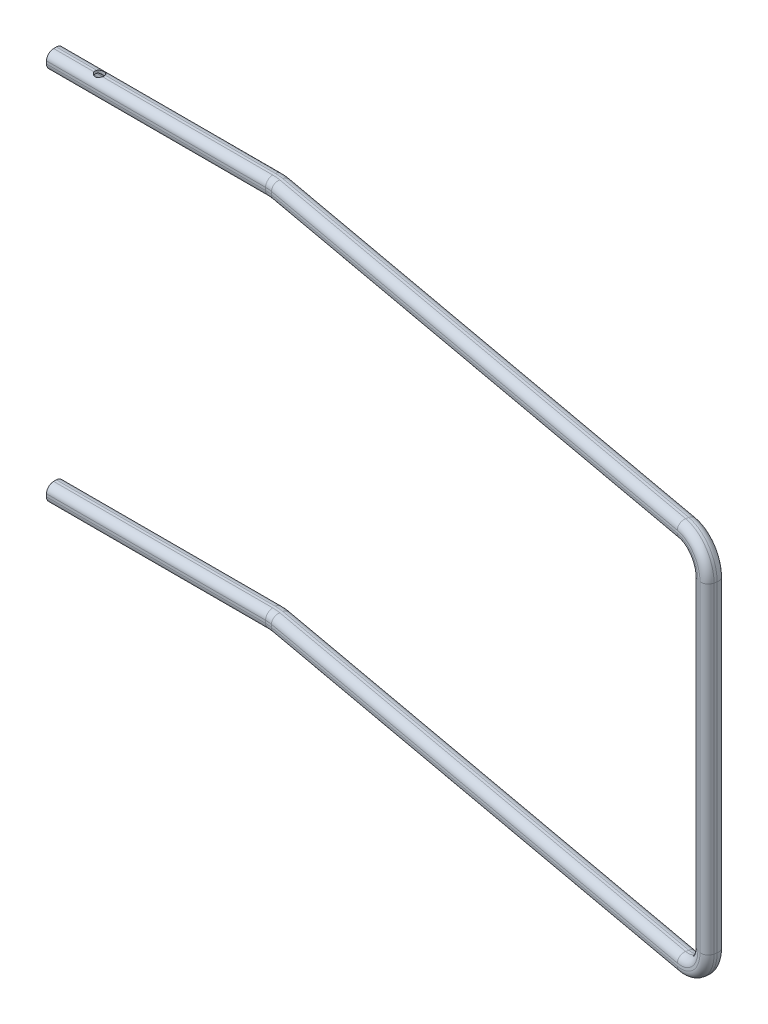
SolidWorks part; units mm, degrees
material "5052-H38, Rod (SS)"
ref_plane "Front Plane" through (0, 0, 0) normal (0, 0, 1) x (1, 0, 0)
ref_plane "Top Plane" through (0, 0, 0) normal (0, 1, 0) x (1, 0, 0)
ref_plane "Right Plane" through (0, 0, 0) normal (1, 0, 0) x (0, 0, -1)
sketch "Sketch2" plane through (0, 0, 0) normal (1, 0, 0) x (0, 0, -1)
  line L1 (-1.5, -6.5) -> (1.5, -6.5)
  line L2 (-6.5, -1.5) -> (-6.5, 1.5)
  line L3 (-1.5, 6.5) -> (1.5, 6.5)
  line L4 (6.5, -1.5) -> (6.5, 1.5)
  line L5 (-6.5, -6.5) -> (6.5, 6.5) construction
  line L6 (-6.5, 6.5) -> (6.5, -6.5) construction
  arc A0 (6.5, -1.5) -> (1.5, -6.5) centre (1.5, -1.5) cw
  arc A1 (-1.5, -6.5) -> (-6.5, -1.5) centre (-1.5, -1.5) cw
  arc A2 (-6.5, 1.5) -> (-1.5, 6.5) centre (-1.5, 1.5) cw
  arc A3 (1.5, 6.5) -> (6.5, 1.5) centre (1.5, 1.5) cw
  point P0 (0, 0)
  dimension "D3" = 5
  dimension "D1" = 13
  dimension "D2" = 13
sketch3d "3DSketch2"
  line L0 (0, 0, 0) -> (840, 0, 0) construction
  line L1 (840, 0, 0) -> (840, -210, 0) construction
  line L2 (840, -210, 0) -> (840, -210, 107.5) construction
  line L3 (0, 0, 0) -> (245.4821, 0, 0)
  line L4 (254.4447, 0, 0.8098) -> (810.4859, 0, 102.1224)
  line L6 (0, 0, 0) -> (0, -210, 0) construction
  line L7 (840, -210, 107.5) -> (840, -210, 287.5) construction
  line L8 (840, -210, 287.5) -> (-10.0746, -210, 287.5) construction
  line L9 (840, -30, 107.5) -> (840, -210, 107.5)
  arc A0 (254.4447, 0, 0.8098) -> (245.4821, 0, 0) centre (245.4821, 0, 50) ccw
  arc A1 (840, -30, 107.5) -> (810.4859, 0, 102.1224) centre (810.4859, -30, 102.1224) ccw
  point P6 (620, -210, 127.5)
  point P11 (612.739, -219.4022, 135.7204)
  point P16 (250, 0, 0)
  point P17 (245.4821, 50, 50)
  point P20 (840, 0, 107.5)
  point P21 (805.1083, -30, 131.6365)
  dimension "5" = 50
  dimension "D9" = 30
  dimension "D1" = 250
  dimension "D3" = 210
  dimension "D4" = 107.5
  dimension "D5" = 210
  dimension "D6" = 840
  dimension "D7" = 180
  dimension "D8" = 210
sweep "Sweep-Thin3" add profiles "Sketch2" path "3DSketch2" parameters "D1"=3
sketch "Sketch21" plane through (0, 0, 0) normal (0, 1, 0) x (1, 0, 0)
  line L0 (0, 0) -> (245.4821, 0) construction
  circle A0 centre (50, 0) radius 5
  dimension "D1" = 10
  dimension "D2" = 50
extrude "Cut-Extrude3" cut sketch "Sketch21" against normal through all both and the other way through all
sketch "Sketch22" [suppressed] plane through (0, 0, 0) normal (0, 0, 1) x (1, 0, 0)
ref_plane "Plane1" [suppressed] through (0, -210, 0) normal (0, 1, 0) x (1, 0, 0)
ref_plane "Plane2" through (0, -210, 0) normal (0, -1, 0) x (-1, 0, 0)
ref_plane "Plane3" through (0, -210, 0) normal (0, -1, 0) x (-1, 0, 0)
mirror "Mirror1" about plane through (0, -210, 0) normal (0, -1, 0) of "Sweep-Thin3"
